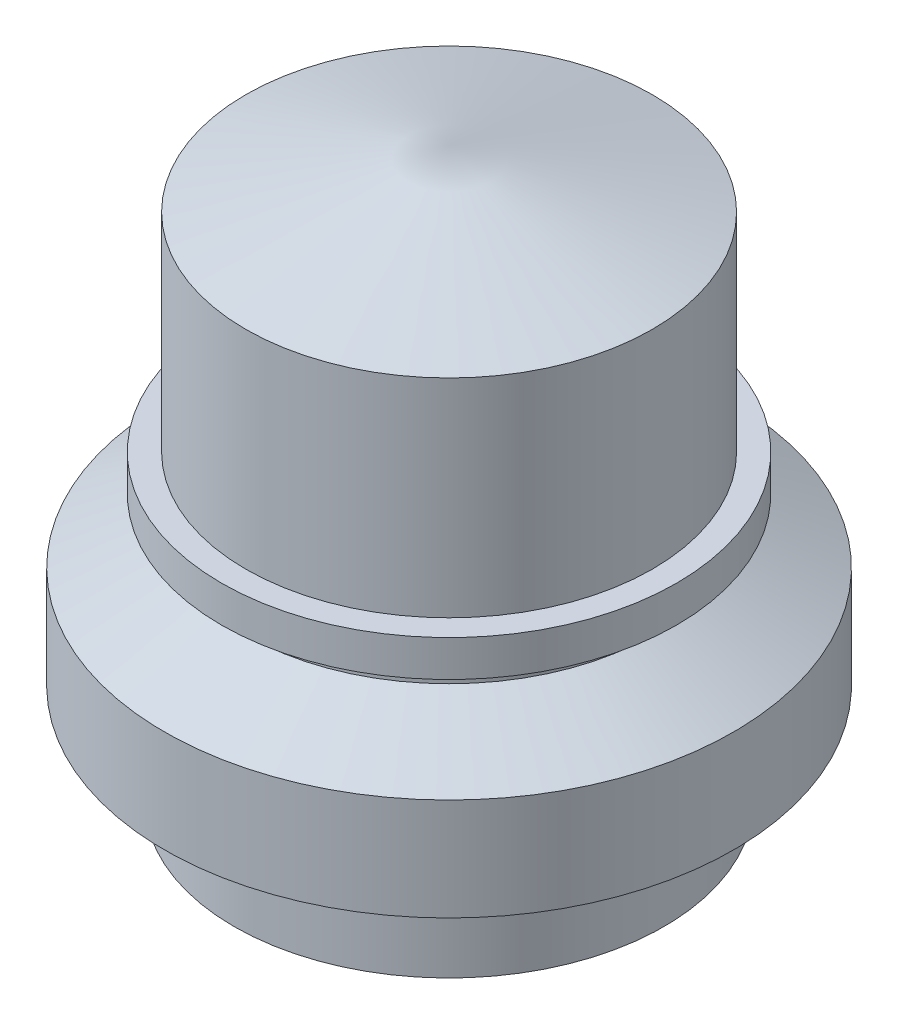
SolidWorks part; units mm, degrees
ref_plane "Alzado" through (0, 0, 0) normal (0, 0, 1) x (1, 0, 0)
ref_plane "Planta" through (0, 0, 0) normal (0, 1, 0) x (1, 0, 0)
ref_plane "Vista lateral" through (0, 0, 0) normal (1, 0, 0) x (0, 0, -1)
sketch "Croquis1" plane through (0, 0, 0) normal (0, 0, 1) x (1, 0, 0)
  line L0 (0, 0) -> (0, 45)
  line L1 (17, 0) -> (17, 8)
  line L2 (22.5, 8) -> (22.5, 16.0779)
  line L3 (17, 8) -> (22.5, 8)
  line L4 (22.5, 16.0779) -> (16.0765, 19.4993)
  line L5 (16.0765, 19.4993) -> (16.0765, 21.1416)
  line L6 (16.0765, 21.1416) -> (17.9925, 21.1416)
  line L7 (17.9925, 21.1416) -> (17.9925, 24.0157)
  line L8 (17.9925, 24.0157) -> (16.0765, 24.0157)
  line L9 (16.0765, 24.0157) -> (16.0765, 40.4387)
  line L10 (16.0765, 40.4387) -> (0, 45)
  line L11 (0, 45) -> (-0.0729, 45.0919)
  line L12 (17, 0) -> (0, 0)
  dimension "D1" = 45
  dimension "D2" = 8
  dimension "D3" = 17
  dimension "D4" = 22.5
revolve "Revolución1" add sketch "Croquis1" angle 360 about L0
